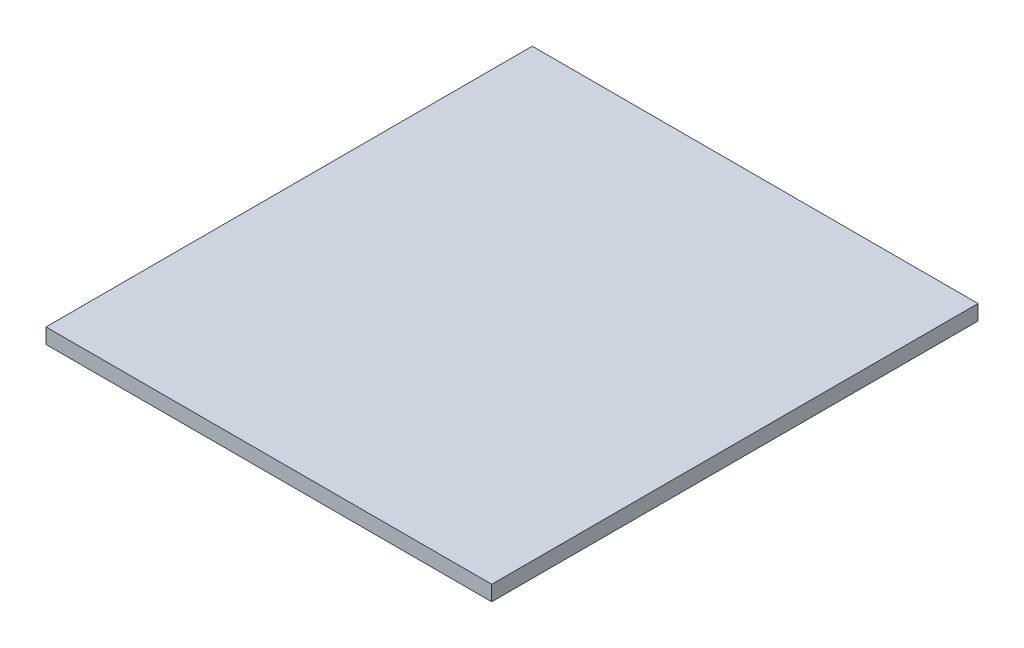
SolidWorks part; units mm, degrees
material "ASTM A36 Steel"
ref_plane "Front Plane" through (0, 0, 0) normal (0, 0, 1) x (1, 0, 0)
ref_plane "Top Plane" through (0, 0, 0) normal (0, 1, 0) x (1, 0, 0)
ref_plane "Right Plane" through (0, 0, 0) normal (1, 0, 0) x (0, 0, -1)
sketch "Sketch1" plane through (0, -127, 0) normal (0, -1, 0) x (1, 0, 0)
  line L0 (-2.5, -130.5984) -> (-2.5, -44.3935) construction
  line L1 (-268.35, 114.3) -> (11.05, 114.3)
  line L2 (-268.35, 114.3) -> (-268.35, -190.5)
  line L3 (-268.35, -190.5) -> (11.05, -190.5)
  line L4 (11.05, 114.3) -> (11.05, -190.5)
  line L5 (-255.65, -38.1) -> (-255.65, 38.1) construction
  line L7 (-206.8438, 101.6) -> (-217.9563, 101.6) construction
  point P12 (11.05, -161.6648)
  point P13 (11.05, -208.2633)
  dimension "D1" = 13.55
  dimension "D2" = 12.7
  dimension "D3" = 12.7
  dimension "D4" = 304.8
  dimension "D5" = 279.4
extrude "Boss-Extrude1" add sketch "Sketch1" along normal blind 9.525
